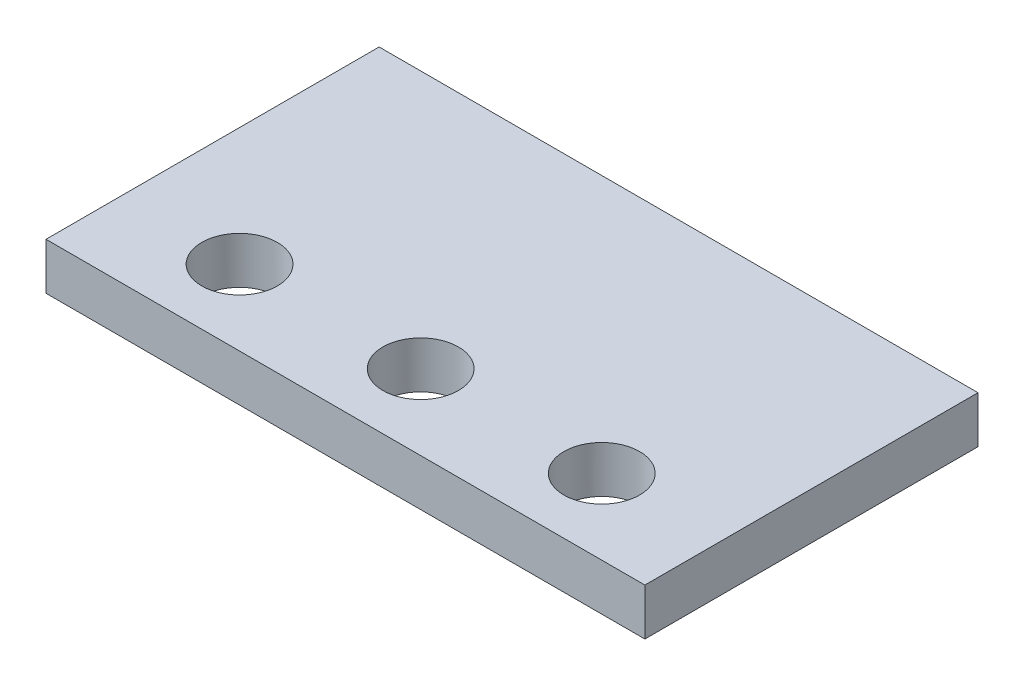
SolidWorks part; units mm, degrees
ref_plane "Alzado" through (0, 0, 0) normal (0, 0, 1) x (1, 0, 0)
ref_plane "Planta" through (0, 0, 0) normal (0, 1, 0) x (1, 0, 0)
ref_plane "Vista lateral" through (0, 0, 0) normal (1, 0, 0) x (0, 0, -1)
ref_plane "Plano2" through (0, 0, 360) normal (0, 0, -1) x (-1, 0, 0)
sketch "Croquis1" plane through (0, 0, 360) normal (0, 0, -1) x (-1, 0, 0)
  line L0 (-152.2459, -167.1656) -> (167.7541, -167.1656)
  line L1 (-177.2459, -167.1656) -> (192.7541, -167.1656) construction
  line L2 (7.7541, -167.1656) -> (7.7541, -33.1806) construction
  line L4 (-152.2459, -167.1656) -> (167.7541, -167.1656)
  line L5 (-152.2459, -167.1656) -> (-152.2459, -142.1656)
  line L6 (-152.2459, -142.1656) -> (167.7541, -142.1656)
  line L7 (167.7541, -167.1656) -> (167.7541, -142.1656)
  point P5 (7.7541, -167.1656)
  dimension "D1" = 320
  dimension "D2" = 25
extrude "Saliente-Extruir1" add sketch "Croquis1" along normal blind 178 contours L0 L2 L6 L5 | L2 L4 L7 L6
sketch "Croquis2" plane through (0, -167.1656, 0) normal (0, -1, 0) x (1, 0, 0)
  line L0 (-7.7541, 360) -> (-7.7541, 340) construction
  line L2 (152.2459, 360) -> (-167.7541, 360) construction
  circle A0 centre (-104.5195, 319.8097) radius 20.1903
  circle A1 centre (-7.7541, 319.8097) radius 20.1903
  circle A2 centre (89.0113, 319.8097) radius 20.1903
  dimension "D1" = 20
  dimension "D2" = 3
extrude "Cortar-Extruir1" cut sketch "Croquis2" against normal up to next contours A2 | A1 | A0
